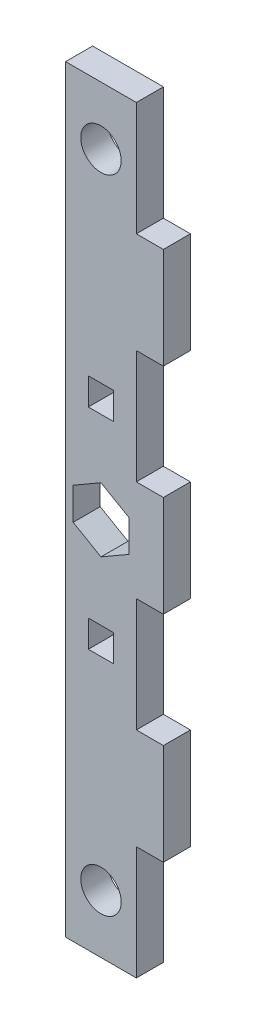
SolidWorks part; units mm, degrees
ref_plane "Front Plane" through (0, 0, 0) normal (0, 0, 1) x (1, 0, 0)
ref_plane "Top Plane" through (0, 0, 0) normal (0, 1, 0) x (1, 0, 0)
ref_plane "Right Plane" through (0, 0, 0) normal (1, 0, 0) x (0, 0, -1)
sketch "Model" plane through (0, 0, 0) normal (0, 0, 1) x (1, 0, 0)
  line L0 (7, 150) -> (7, 0) construction
  line L1 (0, 0) -> (14, 0)
  line L2 (0, 0) -> (0, 150)
  line L3 (0, 150) -> (14, 150)
  line L4 (14, 0) -> (14, 22.5)
  line L5 (0, 75) -> (14, 75) construction
  line L6 (4.5, 51.575) -> (9.5, 56.925) construction
  line L7 (4.5, 93.075) -> (9.5, 93.075)
  line L8 (4.5, 93.075) -> (4.5, 98.425)
  line L9 (4.5, 98.425) -> (9.5, 98.425)
  line L10 (9.5, 93.075) -> (9.5, 98.425)
  line L11 (4.5, 93.075) -> (9.5, 98.425) construction
  line L12 (4.5, 98.425) -> (9.5, 93.075) construction
  line L13 (7, 81.3509) -> (1.5, 78.1754)
  line L14 (1.5, 78.1754) -> (1.5, 71.8246)
  line L15 (1.5, 71.8246) -> (7, 68.6491)
  line L16 (7, 68.6491) -> (12.5, 71.8246)
  line L17 (12.5, 71.8246) -> (12.5, 78.1754)
  line L18 (12.5, 78.1754) -> (7, 81.3509)
  line L19 (4.5, 56.925) -> (9.5, 51.575) construction
  line L20 (9.5, 56.925) -> (9.5, 51.575)
  line L21 (4.5, 51.575) -> (9.5, 51.575)
  line L22 (4.5, 56.925) -> (4.5, 51.575)
  line L23 (4.5, 56.925) -> (9.5, 56.925)
  line L24 (14, 42.5) -> (14, 65)
  line L25 (14, 127.5) -> (19.35, 127.5)
  line L27 (14, 107.5) -> (19.35, 107.5)
  line L28 (19.35, 127.5) -> (19.35, 107.5)
  line L29 (14, 85) -> (19.35, 85)
  line L31 (14, 65) -> (19.35, 65)
  line L32 (19.35, 85) -> (19.35, 65)
  line L33 (14, 22.5) -> (19.35, 22.5)
  line L34 (19.35, 75) -> (14, 75) construction
  line L35 (14, 42.5) -> (19.35, 42.5)
  line L36 (19.35, 22.5) -> (19.35, 42.5)
  line L37 (14, 85) -> (14, 107.5)
  line L38 (14, 127.5) -> (14, 150)
  circle A0 centre (7, 138.5) radius 4
  circle A1 centre (7, 75) radius 5.5 construction
  circle A2 centre (7, 11.5) radius 4
  point P10 (7, 95.75)
  point P27 (7, 54.25)
  dimension "D5" = 8
  dimension "D1" = 150
  dimension "D3" = 14
  dimension "D8" = 11.5
  dimension "D10" = 5
  dimension "D12" = 5.35
  dimension "D14" = 51.575
  dimension "D16" = 11
  dimension "D21" = 20
  dimension "D23" = 5.35
  dimension "D29" = 22.5
  dimension "D31" = 11.7241
extrude "Boss-Extrude1" add sketch "Model" along normal blind 5.35
equation "\"mdfthick\"=5.35"
equation "\"D12@Model\"=\"mdfthick\""
equation "\"D23@Model\"=\"mdfthick\""
equation "\"D1@Boss-Extrude1\"=\"mdfthick\""
